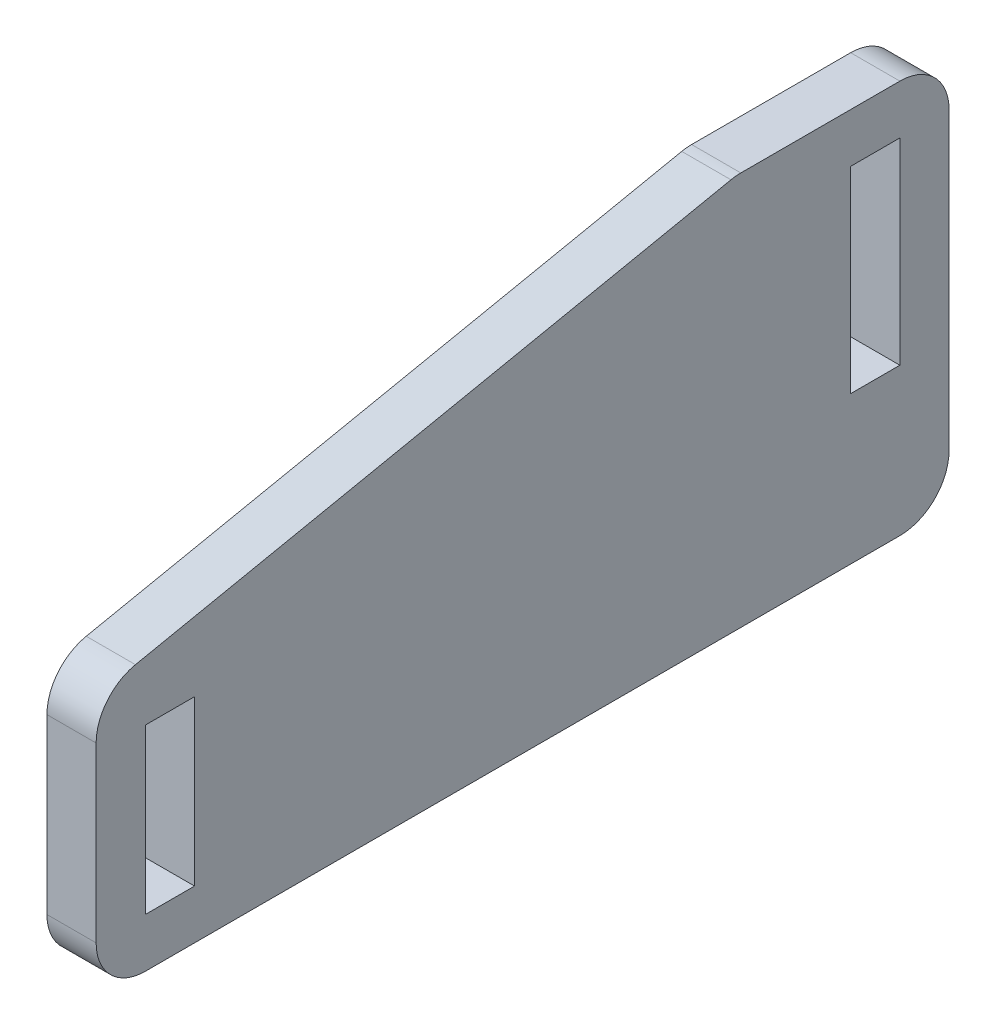
SolidWorks part; units mm, degrees
ref_plane "Спереди" through (0, 0, 0) normal (0, 0, 1) x (1, 0, 0)
ref_plane "Сверху" through (0, 0, 0) normal (0, 1, 0) x (1, 0, 0)
ref_plane "Справа" through (0, 0, 0) normal (1, 0, 0) x (0, 0, -1)
sketch "Эскиз1" plane through (0, 0, 0) normal (1, 0, 0) x (0, 0, -1)
  line L0 (-26, 4) -> (13, 12)
  line L1 (-23, -9) -> (-20, -9)
  line L2 (-23, -9) -> (-23, 1)
  line L3 (-23, 1) -> (-20, 1)
  line L4 (-20, -9) -> (-20, 1)
  line L5 (26, 12) -> (26, -12)
  line L6 (26, -12) -> (-26, -12)
  line L7 (-26, -12) -> (-26, 4)
  line L8 (13, 12) -> (26, 12)
  line L9 (20, -3) -> (23, -3)
  line L10 (20, -3) -> (20, 9)
  line L11 (20, 9) -> (23, 9)
  line L12 (23, -3) -> (23, 9)
extrude "Бобышка-Вытянуть1" add sketch "Эскиз1" along normal blind 3
fillet "Скругление1" radius 3 5 edges at (1.5, -12, 26) (1.5, -12, -26) (1.5, 12, -26) (1.5, 12, -13) (1.5, 4, 26)
